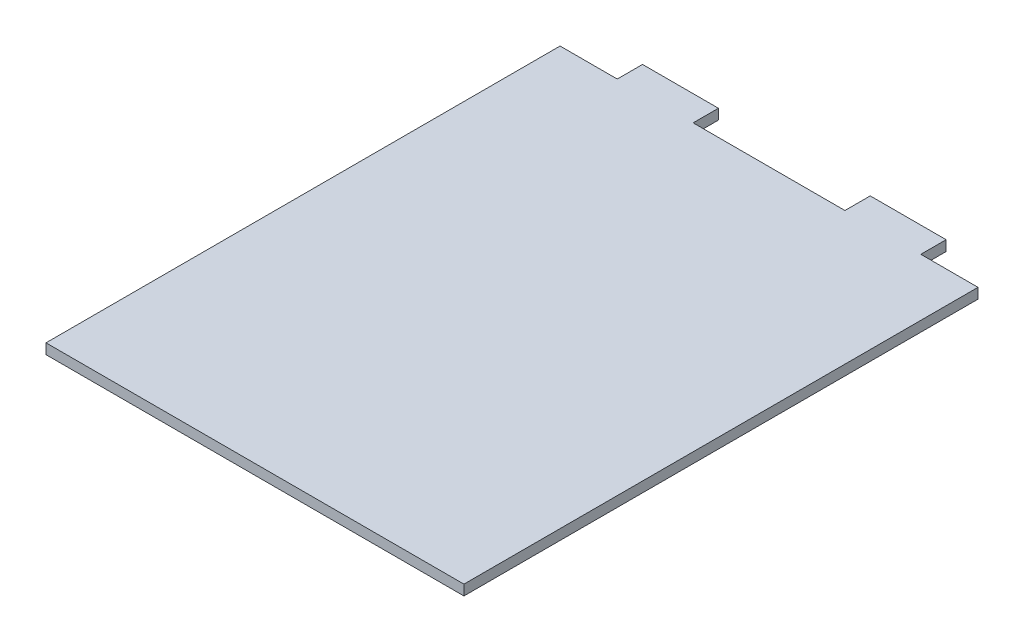
SolidWorks part; units mm, degrees
ref_plane "Front Plane" through (0, 0, 0) normal (0, 0, 1) x (1, 0, 0)
ref_plane "Top Plane" through (0, 0, 0) normal (0, 1, 0) x (1, 0, 0)
ref_plane "Right Plane" through (0, 0, 0) normal (1, 0, 0) x (0, 0, -1)
sketch "Sketch1" plane through (0, 0, 0) normal (0, 1, 0) x (1, 0, 0)
  line L0 (0, 0) -> (0, 203.5635) construction
  line L1 (-206.5, -254) -> (206.5, -254)
  line L2 (-206.5, -254) -> (-206.5, 254)
  line L3 (-206.5, 254) -> (-150, 254)
  line L4 (206.5, -254) -> (206.5, 254)
  line L5 (-206.5, -254) -> (206.5, 254) construction
  line L6 (-206.5, 254) -> (206.5, -254) construction
  line L7 (0, 0) -> (154.4902, 0) construction
  line L8 (-150, 254) -> (-150, 279)
  line L9 (-150, 279) -> (-75, 279)
  line L10 (-75, 279) -> (-75, 254)
  line L11 (75, 279) -> (75, 254)
  line L12 (150, 279) -> (75, 279)
  line L13 (150, 254) -> (150, 279)
  line L14 (150, 254) -> (206.5, 254)
  line L15 (-75, 254) -> (75, 254)
  point P0 (0, 0)
  dimension "D1" = 413
  dimension "508" = 508
  dimension "D3" = 25
  dimension "D4" = 75
  dimension "D5" = 75
extrude "Boss-Extrude1" add sketch "Sketch1" along normal blind 10.16
